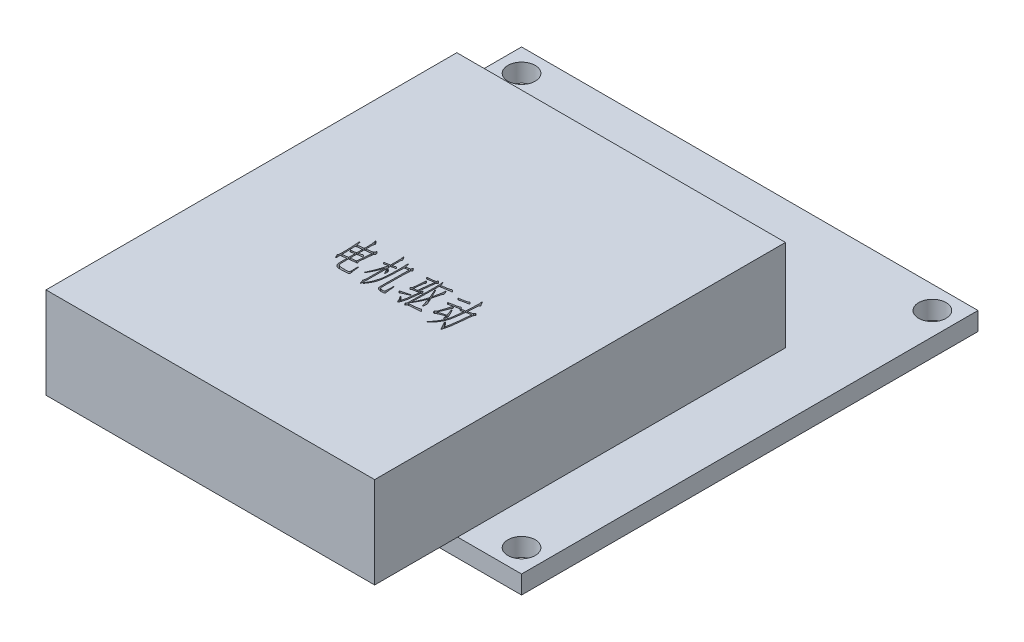
SolidWorks part; units mm, degrees
material "纯金"
ref_plane "前视基准面" through (0, 0, 0) normal (0, 0, 1) x (1, 0, 0)
ref_plane "上视基准面" through (0, 0, 0) normal (0, 1, 0) x (1, 0, 0)
ref_plane "右视基准面" through (0, 0, 0) normal (1, 0, 0) x (0, 0, -1)
sketch "草图1" plane through (0, 0, 0) normal (0, 1, 0) x (1, 0, 0)
  line L1 (-25, -25) -> (25, -25)
  line L2 (-25, -25) -> (-25, 25)
  line L3 (-25, 25) -> (25, 25)
  line L4 (25, -25) -> (25, 25)
  line L5 (-25, -25) -> (25, 25) construction
  line L6 (-25, 25) -> (25, -25) construction
  point P0 (0, 0)
  dimension "D1" = 50
  dimension "D2" = 50
extrude "凸台-拉伸1" add sketch "草图1" along normal blind 2
sketch "草图2" plane through (0, 2, 0) normal (0, 1, 0) x (1, 0, 0)
  line L0 (-25, 25) -> (-25, -25) construction
  line L1 (25, 25) -> (-25, 25) construction
  circle A0 centre (-22.5, 22.5) radius 1.5
  dimension "D1" = 3
  dimension "D2" = 2.5
  dimension "D3" = 2.5
extrude "切除-拉伸1" cut sketch "草图2" against normal through all contours A0
ref_plane "基准面1" through (0, 0, 0) normal (0, 0, -1) x (-1, 0, 0)
ref_plane "基准面2" through (0, 0, 0) normal (-1, 0, 0) x (0, 0, 1)
mirror "镜向1" about plane through (0, 0, 0) normal (0, 0, -1) of "切除-拉伸1"
mirror "镜向2" about plane through (0, 0, 0) normal (-1, 0, 0) of "镜向1", "切除-拉伸1"
sketch "草图6" plane through (0, 2, 0) normal (0, 1, 0) x (1, 0, 0)
  line L1 (-25, 25) -> (-25, -25) construction
  line L2 (-18, 10.9078) -> (18, 10.9078)
  line L3 (-18, 10.9078) -> (-18, -34.0922)
  line L4 (-18, -34.0922) -> (18, -34.0922)
  line L5 (18, 10.9078) -> (18, -34.0922)
  line L6 (-18, 10.9078) -> (18, -34.0922) construction
  line L7 (-18, -34.0922) -> (18, 10.9078) construction
  point P2 (0, -11.5922)
  dimension "D1" = 36
  dimension "D2" = 45
  dimension "D3" = 25
extrude "凸台-拉伸2" add sketch "草图6" along normal blind 10
sketch "草图8" plane through (0, 12, 0) normal (0, 1, 0) x (1, 0, 0)
  text T0 "电机驱动"
extrude "切除-拉伸2" cut sketch "草图8" against normal blind 1
